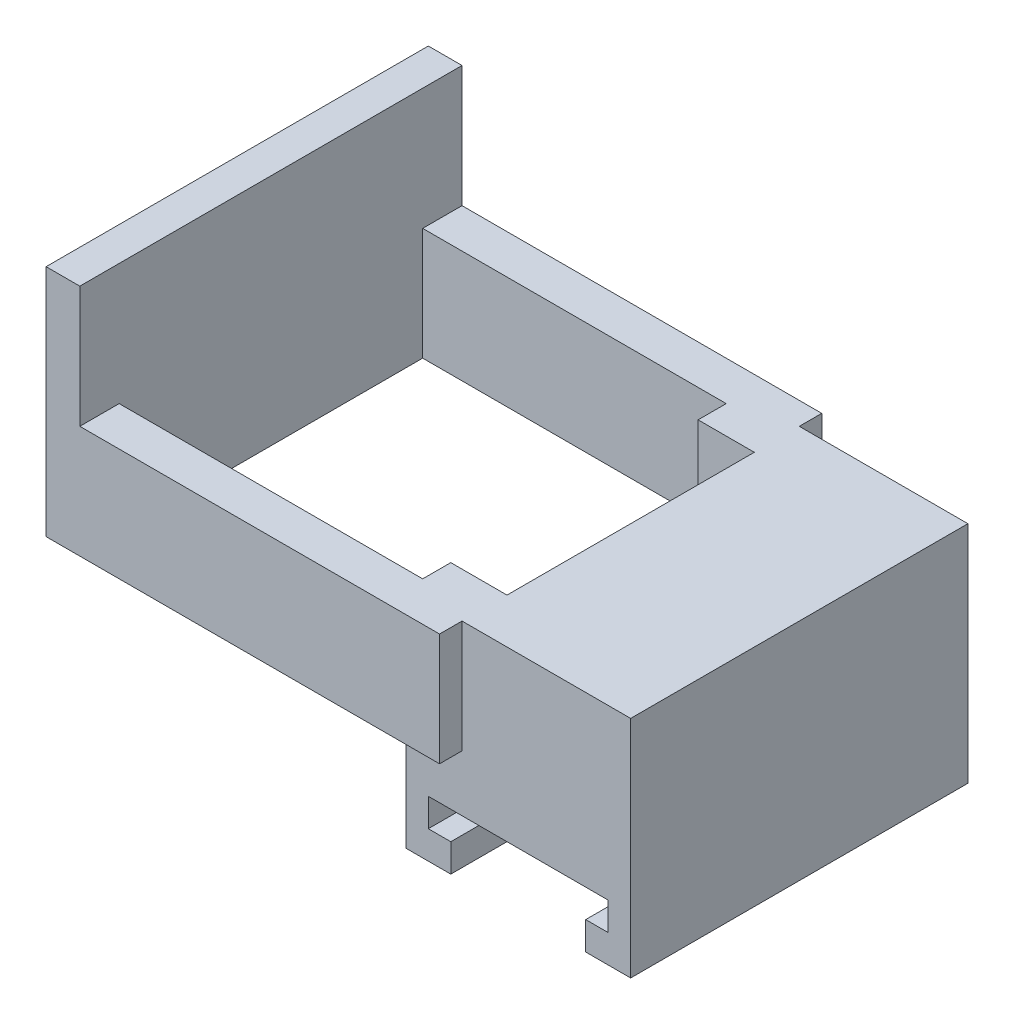
SolidWorks part; units mm, degrees
ref_plane "前视基准面" through (0, 0, 0) normal (0, 0, 1) x (1, 0, 0)
ref_plane "上视基准面" through (0, 0, 0) normal (0, 1, 0) x (1, 0, 0)
ref_plane "右视基准面" through (0, 0, 0) normal (1, 0, 0) x (0, 0, -1)
sketch "草图1" plane through (0, 0, 0) normal (0, 0, 1) x (1, 0, 0)
  line L2 (-19.7321, -1.5982) -> (-11.7321, -1.5982)
  line L3 (-11.7321, -1.5982) -> (-11.7321, 3.4018)
  line L4 (-11.7321, 3.4018) -> (-15.7321, 3.4018)
  line L5 (-15.7321, 3.4018) -> (-15.7321, 8.4018)
  line L6 (-15.7321, 8.4018) -> (16.2679, 8.4018)
  line L7 (0.2679, 8.4018) -> (0.2679, -7.5982) construction
  line L8 (16.2679, 3.4018) -> (16.2679, 8.4018)
  line L9 (12.2679, 3.4018) -> (16.2679, 3.4018)
  line L10 (12.2679, -1.5982) -> (12.2679, 3.4018)
  line L11 (20.2679, -1.5982) -> (12.2679, -1.5982)
  line L13 (-19.7321, -1.5982) -> (-19.7321, 38.4018)
  line L14 (-19.7321, 38.4018) -> (20.2679, 38.4018)
  line L15 (20.2679, 38.4018) -> (20.2679, -1.5982)
extrude "凸台-拉伸1" add sketch "草图1" along normal blind 60
sketch "草图2" plane through (-19.7321, 0, 0) normal (-1, 0, 0) x (0, 0, 1)
  line L0 (60, 38.4018) -> (0, 38.4018) construction
  line L1 (-4, 38.4018) -> (3, 38.4018)
  line L2 (-4, 38.4018) -> (-4, 18.4018)
  line L3 (-4, 18.4018) -> (3, 18.4018)
  line L4 (3, 38.4018) -> (3, 18.4018)
  line L5 (64, 38.4018) -> (57, 38.4018)
  line L6 (64, 38.4018) -> (64, 18.4018)
  line L7 (64, 18.4018) -> (57, 18.4018)
  line L8 (57, 38.4018) -> (57, 18.4018)
  point P4 (0, 0)
  dimension "D1" = 20
  dimension "D2" = 20
extrude "凸台-拉伸2" add sketch "草图2" along normal blind 54
sketch "草图3" plane through (-19.7321, 0, 0) normal (1, 0, 0) x (0, 0, -1)
  line L1 (-64, 38.4018) -> (-60, 38.4018)
  line L2 (-64, 38.4018) -> (-64, 18.4018)
  line L3 (-64, 18.4018) -> (-60, 18.4018)
  line L4 (-60, 38.4018) -> (-60, 18.4018)
  line L5 (0, 38.4018) -> (4, 38.4018)
  line L6 (0, 38.4018) -> (0, 18.4018)
  line L7 (0, 18.4018) -> (4, 18.4018)
  line L8 (4, 38.4018) -> (4, 18.4018)
extrude "凸台-拉伸3" add sketch "草图3" along normal blind 10
sketch "草图4" plane through (-73.7321, 0, 0) normal (-1, 0, 0) x (0, 0, 1)
  line L1 (-4, 18.4018) -> (64, 18.4018)
  line L2 (-4, 18.4018) -> (-4, 60)
  line L3 (-4, 60) -> (64, 60)
  line L4 (64, 18.4018) -> (64, 60)
extrude "凸台-拉伸4" add sketch "草图4" along normal blind 6
sketch "草图5" plane through (-19.7321, 0, 0) normal (-1, 0, 0) x (0, 0, 1)
  line L1 (8, 13.4018) -> (52, 13.4018)
  line L2 (8, 13.4018) -> (8, 38.5821)
  line L3 (8, 38.5821) -> (52, 38.5821)
  line L4 (52, 13.4018) -> (52, 38.5821)
  line L7 (60, -1.5982) -> (0, -1.5982) construction
  line L8 (0, 18.4018) -> (0, -1.5982) construction
  line L9 (60, 18.4018) -> (60, -1.5982) construction
  dimension "D1" = 15
  dimension "D3" = 8
  dimension "D4" = 8
extrude "切除-拉伸1" cut sketch "草图5" against normal blind 10
